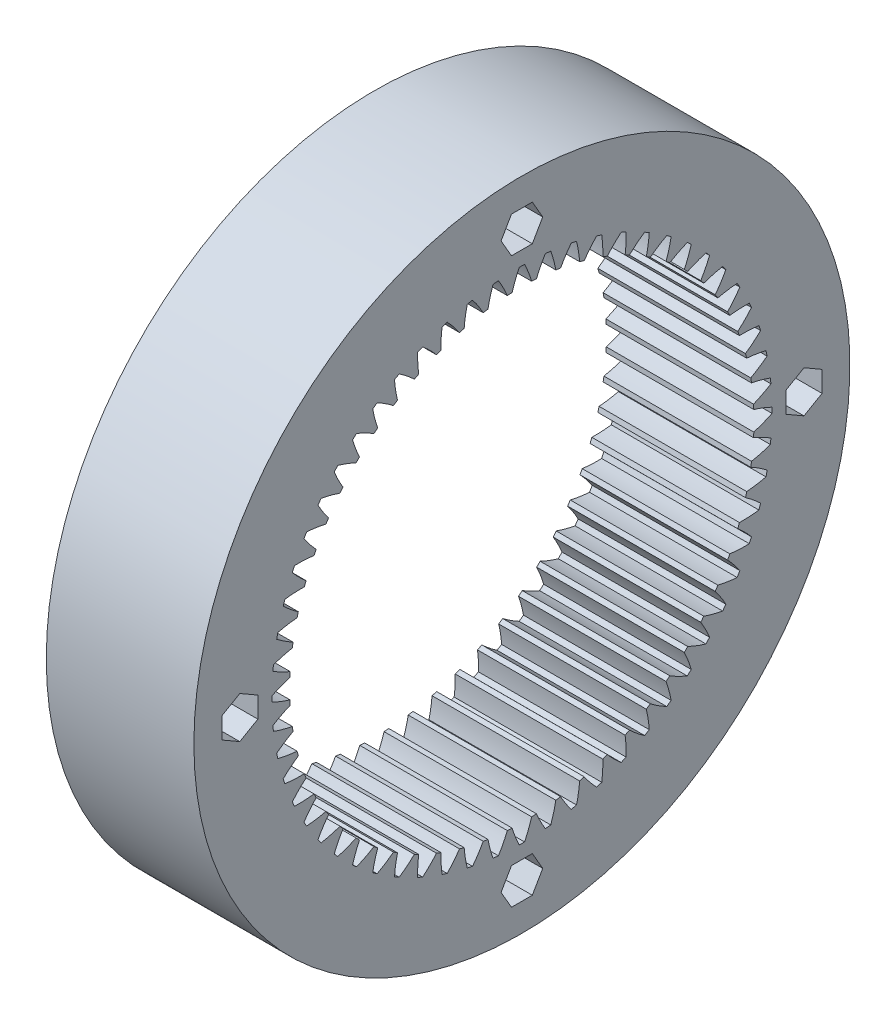
SolidWorks part; units mm, degrees
ref_plane "Plane1" through (0, 0, 0) normal (0, 0, 1) x (1, 0, 0)
ref_plane "Plane2" through (0, 0, 0) normal (0, 1, 0) x (1, 0, 0)
ref_plane "Plane3" through (0, 0, 0) normal (1, 0, 0) x (0, 0, -1)
sketch "HoldingSke" plane through (0, 0, 0) normal (0, 1, 0) x (1, 0, 0)
  line L0 (0, 0) -> (0.4098, -0.7099)
  line L1 (-15, 0) -> (100, 0) construction
  line L2 (0, 0) -> (-2.1039, 2.3779)
  line L3 (0, 0) -> (-11.863, 4.5341)
  line L4 (0, 0) -> (4.318, 7.479)
  line L5 (0, 0) -> (-23.7986, -8.8762)
  line L6 (0, 0) -> (-10.5278, -7.1032)
  line L7 (-2.1039, 2.3779) -> (3.3635, 27.1825)
  line L8 (-76.2, 3.5979) -> (-54.61, 3.5979)
  line L9 (-71.009, 38.7566) -> (-53.1078, 45.2721)
  line L10 (-76.2, 71.12) -> (104.1128, 71.12)
  line L11 (0, 0) -> (-22.5, 0)
  line L12 (-76.2, 101.6) -> (-76.155, 101.6)
  line L13 (24.9733, 27.94) -> (52.9518, 28.4284)
  line L14 (24.9733, 27.94) -> (24.9743, 27.94)
  line L15 (24.9733, 27.94) -> (100.4006, 29.5858)
  circle A0 centre (0, 0) radius 50
  circle A1 centre (0, 0) radius 12.7
  circle A2 centre (0, 0) radius 12.7
  dimension "MHD" = 25.4
  dimension "Hub_dia" = 25.4
  dimension "Diameter" = 100
  dimension "Num_teeth" = 60
  dimension "Pitch" = 0.8197
  dimension "Overall_len" = 25.4
  dimension "Show_teeth" = 60
  dimension "Thickness" = 12.7
  dimension "OAL" = 25.4001
  dimension "T_dim" = 21.59
  dimension "Ap" = 20
  dimension "H" = 19.05
  dimension "Pitch_radius" = 180.3128
  dimension "Width" = 22.5
  dimension "Backlash" = 0.045
  dimension "Addendum_fac" = 1
  dimension "Dedendum_fac" = 1.25
  dimension "Clearance_fac" = 0.25
  dimension "Dedendum_add" = 0.001
  dimension "Module" = 1.22
sketch "BasProSke" plane through (0, 0, 0) normal (0, 1, 0) x (1, 0, 0)
  line L0 (-10, 0) -> (60, 0) construction
  line L1 (0, 35.38) -> (0, 50)
  line L2 (0, 35.38) -> (22.5, 35.38)
  line L3 (22.5, 35.38) -> (22.5, 50)
  line L4 (22.5, 50) -> (0, 50)
  dimension "Diameter" = 100
  dimension "Thickness" = 22.5
  dimension "Inside_diameter" = 70.76
revolve "Base-Revolve" add sketch "BasProSke" angle 360 about L0
sketch "TooCutSke" plane through (0, 0, 0) normal (1, 0, 0) x (0, 0, -1)
  line L3 (1.0706, 36.5843) -> (1.0706, 53.6633) construction
  line L4 (0, 0) -> (0, 59.563) construction
  line L5 (0, 0) -> (-3.576, 68.2339) construction
  line L6 (-16.0625, 30.1542) -> (36.171, 32.8916) construction
  circle A0 centre (0, 0) radius 36.6 construction
  circle A1 centre (0, 0) radius 38.126 construction
  circle A2 centre (0, 0) radius 30.9535 construction
  circle A3 centre (0, 0) radius 35.3546 construction
  arc A4 (1.4923, 35.3231) -> (0.411, 38.1238) centre (-16.0625, 30.1542) ccw
  arc A5 (1.4923, 35.3231) -> (-1.4923, 35.3231) centre (0, 0) ccw
  arc A6 (0.411, 38.1238) -> (-0.411, 38.1238) centre (0, 0) ccw
  arc A7 (-0.411, 38.1238) -> (-1.4923, 35.3231) centre (16.0625, 30.1542) ccw
  dimension "Pitch_dia" = 73.2
  dimension "Base_dia" = 61.9069
  dimension "Root_dia" = 76.252
  dimension "Overcut_dia" = 70.7092
  dimension "Flank_rad" = 18.3
  dimension "Half_ang" = 3
  dimension "Half_CT" = 1.0706
extrude "ToothCut" cut sketch "TooCutSke" along normal through all
fillet "Breaks" [suppressed] radius 0.122
fillet "RootFillets" [suppressed] radius 0.306
pattern_circular "TeethCuts" count 60 every 6 about axis through (-10, 0, 0) along (1, 0, 0) of "RootFillets", "Breaks", "ToothCut"
sketch "Sketch3" plane through (0, 0, 0) normal (-1, 0, 0) x (0, 0, 1)
  circle A0 centre (0, 0) radius 43 construction
  circle A1 centre (43, 0) radius 1.6
  circle A2 centre (0, 43) radius 1.6
  circle A3 centre (0, -43) radius 1.6
  circle A4 centre (-43, 0) radius 1.6
  dimension "D1" = 3.2
  dimension "D2" = 86
extrude "Cut-Extrude2" cut sketch "Sketch3" against normal through all
sketch "Sketch4" plane through (22.5, 0, 0) normal (1, 0, 0) x (0, 0, -1)
  line L1 (1.5877, -40.25) -> (-1.5877, -40.25)
  line L2 (-1.5877, -40.25) -> (-3.1754, -43)
  line L3 (-3.1754, -43) -> (-1.5877, -45.75)
  line L4 (-1.5877, -45.75) -> (1.5877, -45.75)
  line L5 (1.5877, -45.75) -> (3.1754, -43)
  line L6 (3.1754, -43) -> (1.5877, -40.25)
  line L7 (43, 3.1754) -> (40.25, 1.5877)
  line L8 (40.25, 1.5877) -> (40.25, -1.5877)
  line L9 (40.25, -1.5877) -> (43, -3.1754)
  line L10 (43, -3.1754) -> (45.75, -1.5877)
  line L11 (45.75, -1.5877) -> (45.75, 1.5877)
  line L12 (45.75, 1.5877) -> (43, 3.1754)
  line L13 (3.1754, 43) -> (1.5877, 45.75)
  line L14 (1.5877, 45.75) -> (-1.5877, 45.75)
  line L15 (-1.5877, 45.75) -> (-3.1754, 43)
  line L16 (-3.1754, 43) -> (-1.5877, 40.25)
  line L17 (-1.5877, 40.25) -> (1.5877, 40.25)
  line L18 (1.5877, 40.25) -> (3.1754, 43)
  line L19 (-43, 3.1754) -> (-45.75, 1.5877)
  line L20 (-45.75, 1.5877) -> (-45.75, -1.5877)
  line L21 (-45.75, -1.5877) -> (-43, -3.1754)
  line L22 (-43, -3.1754) -> (-40.25, -1.5877)
  line L23 (-40.25, -1.5877) -> (-40.25, 1.5877)
  line L24 (-40.25, 1.5877) -> (-43, 3.1754)
  circle A0 centre (43, 0) radius 2.75 construction
  circle A1 centre (0, -43) radius 2.75 construction
  circle A2 centre (0, 43) radius 2.75 construction
  circle A3 centre (-43, 0) radius 2.75 construction
  dimension "D1" = 5.5
extrude "Cut-Extrude3" cut sketch "Sketch4" against normal blind 10
equation "' \"Module@HoldingSke\" = 6.35"
equation "' \"Num_teeth@HoldingSke\" = 24"
equation "' \"Ap@HoldingSke\" =  14.5"
equation "' \"Ap@HoldingSke\" = 14.5"
equation "' \"Width@HoldingSke\" = 12"
equation "' \"Diameter@HoldingSke\" = 8 * 25.4"
equation "' \"Show_teeth@HoldingSke\" = 100"
equation "' \"Backlash@HoldingSke\" = 0.009 * 25.4"
equation "' \"Addendum_fac@HoldingSke\" = 1.0"
equation "' \"Dedendum_fac@HoldingSke\" = 1.25"
equation "' \"Dedendum_add@HoldingSke\" = 0.00005 * 25.4"
equation "' \"Clearance_fac@HoldingSke\" = 0.25"
equation "\"Pitch@HoldingSke\" = 1 / \"Module@HoldingSke\" "
equation "\"Overcut_dia@TooCutSke\" = (\"Num_teeth@HoldingSke\" - 2 * \"Addendum_fac@HoldingSke\") / \"Pitch@HoldingSke\" - 0.002 * 25.4"
equation "\"Pitch_dia@TooCutSke\" = \"Num_teeth@HoldingSke\" / \"Pitch@HoldingSke\""
equation "\"Base_dia@TooCutSke\" = \"Num_teeth@HoldingSke\" / \"Pitch@HoldingSke\" * cos((\"Ap@HoldingSke\"  * 3.14159265 / 180)) * 0.90"
equation "\"Root_dia@TooCutSke\" = \"Num_teeth@HoldingSke\"  / \"Pitch@HoldingSke\" + 2 *  \"Dedendum_fac@HoldingSke\"/ \"Pitch@HoldingSke\" + \"Dedendum_add@HoldingSke\" * 2"
equation "\"Half_ang@TooCutSke\" = 180 / \"Num_teeth@HoldingSke\""
equation "\"Half_CT@TooCutSke\" = \"Num_teeth@HoldingSke\" / \"Pitch@HoldingSke\" * sin((3.14159265 / 2 / \"Num_teeth@HoldingSke\")) / 2 + 10 * \"Backlash@HoldingSke\" / 4"
equation "\"Flank_rad@TooCutSke\" = \"Num_teeth@HoldingSke\" / \"Pitch@HoldingSke\" / 4"
equation "\"Radius@RootFillets\"= \"Clearance_fac@HoldingSke\" / \"Pitch@HoldingSke\" + \"Dedendum_add@HoldingSke\""
equation "\"Break_rad@Breaks\" = 0.02 / \"Pitch@HoldingSke\" * 5"
equation "\"Num_teeth@TeethCuts\" = int( \"Show_teeth@HoldingSke\" ) + 1"
equation "\"Num_teeth@TeethCuts\" = ((sgn( \"Num_teeth@TeethCuts\" - \"Num_teeth@HoldingSke\" )-1)*( \"Num_teeth@TeethCuts\" - \"Num_teeth@HoldingSke\" ))/-2+ \"Num_teeth@HoldingSke\""
equation "\"Num_teeth@TeethCuts\" = ((sgn( \"Num_teeth@TeethCuts\" - 2.0)+1)*( \"Num_teeth@TeethCuts\" - 2.0))/2 +2.0"
equation "\"Angle@TeethCuts\" = 360.0 / \"Num_teeth@HoldingSke\""
equation "\"Diameter@BasProSke\" = \"Num_teeth@HoldingSke\"  / \"Pitch@HoldingSke\" + 2 *  \"Dedendum_fac@HoldingSke\"/ \"Pitch@HoldingSke\" + \"Dedendum_add@HoldingSke\" * 2 + 0.002 * 25.4"
equation "\"Diameter@BasProSke\" = ((sgn( \"Diameter@BasProSke\"  - \"Diameter@HoldingSke\" )+1)*( \"Diameter@BasProSke\"  - \"Diameter@HoldingSke\" ))/2 + \"Diameter@HoldingSke\""
equation "\"Inside_diameter@BasProSke\" =  (\"Num_teeth@HoldingSke\" - 2 * \"Addendum_fac@HoldingSke\") / \"Pitch@HoldingSke\" "
equation "\"Thickness@BasProSke\"  = \"Width@HoldingSke\""
